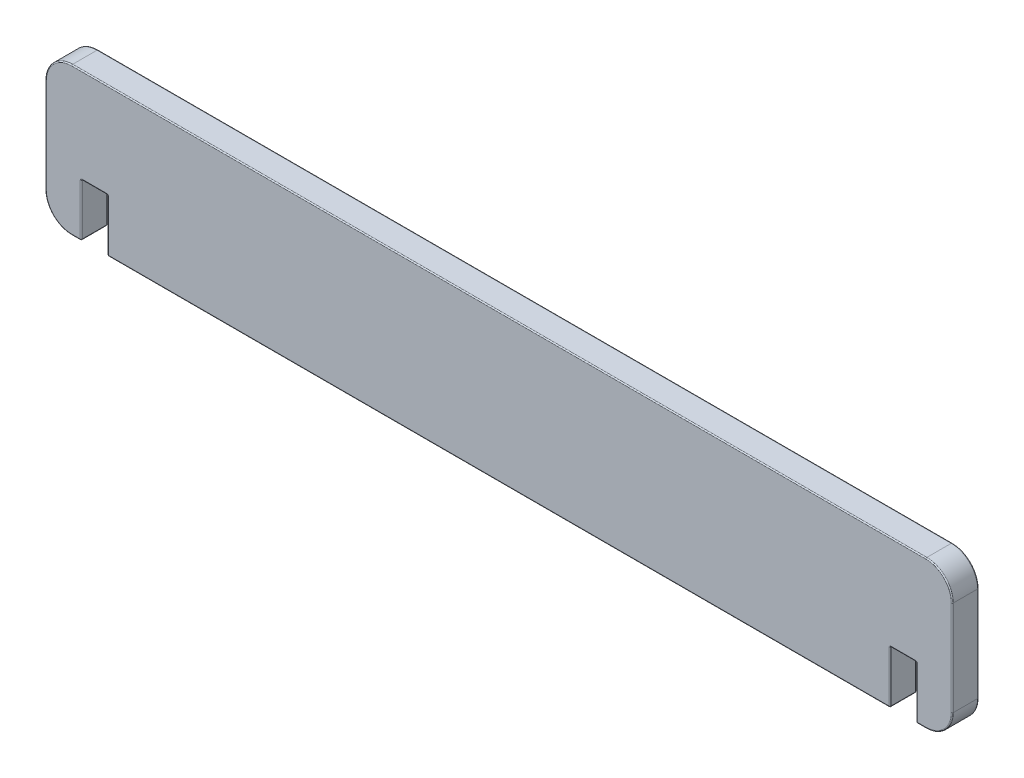
SolidWorks part; units mm, degrees
ref_plane "Plano frontal" through (0, 0, 0) normal (0, 0, 1) x (1, 0, 0)
ref_plane "Plano superior" through (0, 0, 0) normal (0, 1, 0) x (1, 0, 0)
ref_plane "Plano direito" through (0, 0, 0) normal (1, 0, 0) x (0, 0, -1)
sketch "Esboço1" plane through (0, 0, 0) normal (0, 0, 1) x (1, 0, 0)
  line L66 (-93.4548, 163.7347) -> (-12.4548, 163.7347)
  line L67 (-95.9548, 161.2347) -> (-95.9548, 152.2347)
  line L68 (-93.4548, 149.7347) -> (-12.4548, 149.7347)
  line L69 (-9.9548, 161.2347) -> (-9.9548, 152.2347)
  line L70 (-92.5548, 154.7347) -> (-90.0548, 154.7347)
  line L71 (-92.5548, 154.7347) -> (-92.5548, 149.7347)
  line L72 (-92.5548, 149.7347) -> (-90.0548, 149.7347)
  line L73 (-90.0548, 154.7347) -> (-90.0548, 149.7347)
  line L74 (-13.3548, 149.7347) -> (-15.8548, 149.7347)
  line L75 (-13.3548, 149.7347) -> (-13.3548, 154.7347)
  line L76 (-13.3548, 154.7347) -> (-15.8548, 154.7347)
  line L77 (-15.8548, 149.7347) -> (-15.8548, 154.7347)
  line L78 (-66.9548, 149.7347) -> (-64.4548, 149.7347)
  line L79 (-66.9548, 149.7347) -> (-66.9548, 146.2347)
  line L80 (-66.9548, 146.2347) -> (-64.4548, 146.2347)
  line L81 (-64.4548, 149.7347) -> (-64.4548, 146.2347)
  line L82 (-41.4548, 149.7347) -> (-38.9548, 149.7347)
  line L83 (-41.4548, 149.7347) -> (-41.4548, 146.2347)
  line L84 (-41.4548, 146.2347) -> (-38.9548, 146.2347)
  line L85 (-38.9548, 149.7347) -> (-38.9548, 146.2347)
  arc A16 (-12.4548, 163.7347) -> (-9.9548, 161.2347) centre (-12.4548, 161.2347) cw
  arc A17 (-12.4548, 149.7347) -> (-9.9548, 152.2347) centre (-12.4548, 152.2347) ccw
  arc A18 (-93.4548, 163.7347) -> (-95.9548, 161.2347) centre (-93.4548, 161.2347) ccw
  arc A19 (-95.9548, 152.2347) -> (-93.4548, 149.7347) centre (-93.4548, 152.2347) ccw
  point P123 (-52.9548, 163.7347)
  dimension "D42" = 2.5
  dimension "D38" = 74.2
  dimension "D39" = 37.1
  dimension "D40" = 2.5
  dimension "D41" = 5
  dimension "D43" = 23
  dimension "D44" = 2.5
  dimension "D45" = 3.5
  dimension "D46" = 11.5
extrude "Ressalto-extrusão1" add sketch "Esboço1" along normal blind 2.5 contours L67 A19 L68 L71 L70 L73 L77 L76 L75 A17 L69 A16 L66 A18
fillet "Filete1" radius 0.1 40 edges at (-92.5548, 149.7347, 1.25) (-92.5548, 154.7347, 1.25) (-90.0548, 154.7347, 1.25) (-90.0548, 149.7347, 1.25) (-15.8548, 149.7347, 1.25) (-15.8548, 154.7347, 1.25) (-13.3548, 154.7347, 1.25) (-13.3548, 149.7347, 1.25) (-95.2226, 163.0025, 2.5) (-52.9548, 163.7347, 2.5) (-10.687, 163.0025, 2.5) (-9.9548, 156.7347, 2.5) (-10.687, 150.4669, 2.5) (-12.9048, 149.7347, 2.5) (-13.3548, 152.2347, 2.5) (-14.6048, 154.7347, 2.5) (-15.8548, 152.2347, 2.5) (-52.9548, 149.7347, 2.5) (-90.0548, 152.2347, 2.5) (-91.3048, 154.7347, 2.5) (-92.5548, 152.2347, 2.5) (-93.0048, 149.7347, 2.5) (-95.2226, 150.4669, 2.5) (-95.9548, 156.7347, 2.5) (-95.2226, 150.4669, 0) (-93.0048, 149.7347, 0) (-92.5548, 152.2347, 0) (-91.3048, 154.7347, 0) (-90.0548, 152.2347, 0) (-52.9548, 149.7347, 0) (-15.8548, 152.2347, 0) (-14.6048, 154.7347, 0) (-13.3548, 152.2347, 0) (-12.9048, 149.7347, 0) (-10.687, 150.4669, 0) (-9.9548, 156.7347, 0) (-10.687, 163.0025, 0) (-52.9548, 163.7347, 0) (-95.2226, 163.0025, 0) (-95.9548, 156.7347, 0)
